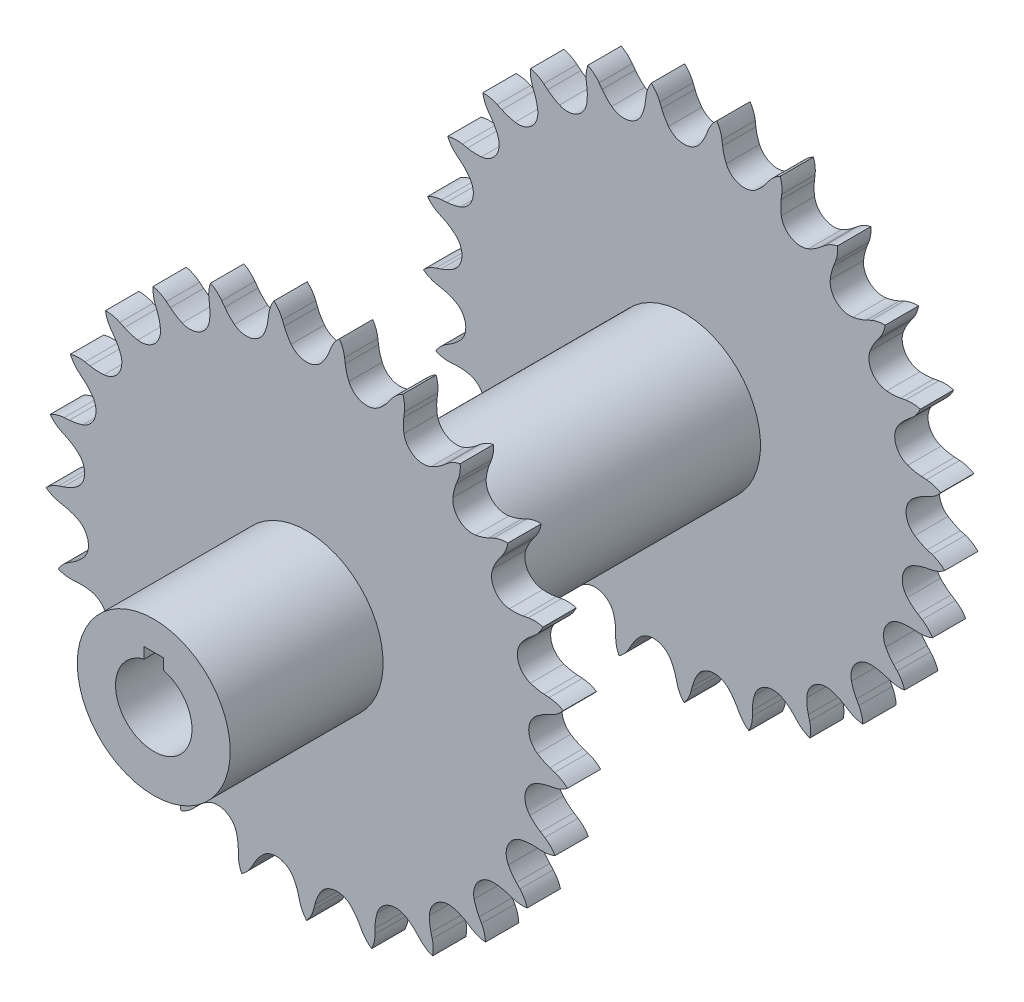
SolidWorks part; units mm, degrees
material "AISI 316 Annealed Stainless Steel Bar (SS)"
ref_plane "Front Plane" through (0, 0, 0) normal (0, 0, 1) x (1, 0, 0)
ref_plane "Top Plane" through (0, 0, 0) normal (0, 1, 0) x (1, 0, 0)
ref_plane "Right Plane" through (0, 0, 0) normal (1, 0, 0) x (0, 0, -1)
sketch "Sketch1" plane through (0, 0, 0) normal (0, 0, 1) x (1, 0, 0)
  line L0 (0, 0) -> (0, 161.8828) construction
  line L1 (6.457, 63.33) -> (6.457, 68.267) construction
  line L2 (89.5524, 63.33) -> (-95.4437, 63.33) construction
  line L3 (6.457, 68.267) -> (0, 68.267)
  line L4 (6.457, 68.267) -> (-4.0675, 60.2204)
  line L5 (6.457, 68.267) -> (-5.8796, 63.3726)
  line L6 (5.8574, 63.3814) -> (6.3512, 64.626)
  line L7 (-5.8574, 63.3814) -> (-6.3512, 64.626)
  line L8 (-14.112, 63.33) -> (-14.112, 61.547) construction
  line L9 (-14.112, 61.547) -> (0, 61.547) construction
  line L10 (0, 0) -> (-19.9508, 157.9268) construction
  line L11 (10.0889, 62.8469) -> (9.9202, 64.1751)
  line L12 (21.4357, 59.9335) -> (22.2235, 61.0162)
  line L13 (25.4014, 58.3634) -> (25.5682, 59.6919)
  line L14 (35.6671, 52.7197) -> (36.6994, 53.5725)
  line L15 (39.1177, 50.2127) -> (39.6097, 51.458)
  line L16 (47.6574, 42.1934) -> (48.8693, 42.7626)
  line L17 (50.3762, 38.907) -> (51.1624, 39.9908)
  line L18 (56.6533, 29.0159) -> (57.9687, 29.2659)
  line L19 (58.4693, 25.1567) -> (59.5004, 26.0109)
  line L20 (62.0894, 14.0152) -> (63.4256, 13.9302)
  line L21 (62.8886, 9.8256) -> (64.0997, 10.3965)
  line L22 (63.6242, -1.8661) -> (64.8973, -2.2807)
  line L23 (63.3563, -6.1228) -> (64.6714, -5.871)
  line L24 (61.1612, -17.6302) -> (62.2912, -18.3484)
  line L25 (59.8432, -21.6866) -> (61.1795, -21.7697)
  line L26 (54.8553, -32.2864) -> (55.7712, -33.2631)
  line L27 (52.5699, -35.8876) -> (53.8436, -36.3005)
  line L28 (45.1026, -44.9141) -> (45.7468, -46.0878)
  line L29 (41.9934, -47.8338) -> (43.1244, -48.5504)
  line L30 (32.5159, -54.7196) -> (32.848, -56.0167)
  line L31 (28.7783, -56.7743) -> (29.6956, -57.7497)
  line L32 (17.8862, -61.0868) -> (17.8852, -62.4258)
  line L33 (13.755, -62.1475) -> (14.4009, -63.3204)
  line L34 (2.1326, -63.6158) -> (1.7987, -64.9124)
  line L35 (-2.1326, -63.6158) -> (-1.7987, -64.9124)
  line L36 (-13.755, -62.1475) -> (-14.4009, -63.3204)
  line L37 (-17.8862, -61.0868) -> (-17.8852, -62.4258)
  line L38 (-28.7783, -56.7743) -> (-29.6956, -57.7497)
  line L39 (-32.5159, -54.7196) -> (-32.848, -56.0167)
  line L40 (-41.9934, -47.8338) -> (-43.1244, -48.5504)
  line L41 (-45.1026, -44.9141) -> (-45.7468, -46.0878)
  line L42 (-52.5699, -35.8876) -> (-53.8436, -36.3005)
  line L43 (-54.8553, -32.2864) -> (-55.7712, -33.2631)
  line L44 (-59.8432, -21.6866) -> (-61.1795, -21.7697)
  line L45 (-61.1612, -17.6302) -> (-62.2912, -18.3484)
  line L46 (-63.3563, -6.1228) -> (-64.6714, -5.871)
  line L47 (-63.6242, -1.8661) -> (-64.8973, -2.2807)
  line L48 (-62.8886, 9.8256) -> (-64.0997, 10.3965)
  line L49 (-62.0894, 14.0152) -> (-63.4256, 13.9302)
  line L50 (-58.4693, 25.1567) -> (-59.5004, 26.0109)
  line L51 (-56.6533, 29.0159) -> (-57.9687, 29.2659)
  line L52 (-50.3762, 38.907) -> (-51.1624, 39.9908)
  line L53 (-47.6574, 42.1934) -> (-48.8693, 42.7626)
  line L54 (-39.1177, 50.2127) -> (-39.6097, 51.458)
  line L55 (-35.6671, 52.7197) -> (-36.6994, 53.5725)
  line L56 (-25.4014, 58.3634) -> (-25.5682, 59.6919)
  line L57 (-21.4357, 59.9335) -> (-22.2235, 61.0162)
  line L58 (-10.0889, 62.8469) -> (-9.9202, 64.1751)
  circle A0 centre (0, 0) radius 63.33 construction
  arc A1 (-5.1081, 63.6787) -> (-5.1158, 63.123) centre (0, 63.33) ccw
  arc A3 (-4.0675, 60.2204) -> (-5.8574, 63.3814) centre (6.457, 68.267) cw
  arc A5 (-4.0675, 60.2204) -> (4.0675, 60.2204) centre (0, 63.33) ccw
  arc A6 (-6.3512, 64.626) -> (-8.5633, 67.7858) centre (-14.112, 61.547) ccw
  arc A7 (4.0675, 60.2204) -> (5.8574, 63.3814) centre (-6.457, 68.267) ccw
  arc A8 (6.3512, 64.626) -> (8.5633, 67.7858) centre (14.112, 61.547) cw
  arc A9 (18.9159, 57.3169) -> (21.4357, 59.9335) centre (10.7232, 67.7281) ccw
  arc A10 (11.0365, 59.34) -> (18.9159, 57.3169) centre (15.7495, 61.3404) ccw
  arc A11 (11.0365, 59.34) -> (10.0889, 62.8469) centre (23.2315, 64.5165) cw
  arc A12 (22.2235, 61.0162) -> (25.152, 63.5266) centre (28.9748, 56.1039) cw
  arc A13 (9.9202, 64.1751) -> (8.5633, 67.7858) centre (1.6375, 63.1229) ccw
  arc A14 (32.5758, 50.812) -> (35.6671, 52.7197) centre (27.2296, 62.9335) ccw
  arc A15 (25.447, 54.7311) -> (32.5758, 50.812) centre (30.5095, 55.4965) ccw
  arc A16 (25.447, 54.7311) -> (25.4014, 58.3634) centre (38.5462, 56.7121) cw
  arc A17 (36.6994, 53.5725) -> (40.1602, 55.2758) centre (42.0169, 47.1355) cw
  arc A18 (25.5682, 59.6919) -> (25.152, 63.5266) centre (17.2841, 60.7326) ccw
  arc A19 (44.1888, 41.1144) -> (47.6574, 42.1934) centre (42.025, 54.1846) ccw
  arc A20 (38.2586, 46.6832) -> (44.1888, 41.1144) centre (43.3524, 46.1656) ccw
  arc A21 (38.2586, 46.6832) -> (39.1177, 50.2127) centre (51.4389, 45.3444) cw
  arc A22 (48.8693, 42.7626) -> (52.645, 43.5517) centre (52.419, 35.2055) cw
  arc A23 (39.6097, 51.458) -> (40.1602, 55.2758) centre (31.8446, 54.5262) ccw
  arc A24 (53.0252, 28.8334) -> (56.6533, 29.0159) centre (54.1799, 42.0311) ccw
  arc A25 (48.6663, 35.702) -> (53.0252, 28.8334) centre (53.4713, 33.9339) ccw
  arc A26 (48.6663, 35.702) -> (50.3762, 38.907) centre (61.0996, 31.1275) cw
  arc A27 (57.9687, 29.2659) -> (61.8219, 29.0912) centre (59.5274, 21.0634) cw
  arc A28 (51.1624, 39.9908) -> (52.645, 43.5517) centre (44.4043, 44.8937) ccw
  arc A29 (58.5299, 14.7407) -> (62.0894, 14.0152) centre (62.9305, 27.2366) ccw
  arc A30 (56.0161, 22.4776) -> (58.5299, 14.7407) centre (60.2304, 19.57) ccw
  arc A31 (56.0161, 22.4776) -> (58.4693, 25.1567) centre (66.9211, 14.9547) cw
  arc A32 (63.4256, 13.9302) -> (67.1144, 12.8028) centre (62.8955, 5.5978) cw
  arc A33 (59.5004, 26.0109) -> (61.8219, 29.0912) centre (54.1738, 32.4404) ccw
  arc A34 (60.357, -0.2782) -> (63.6242, -1.8661) centre (67.7269, 10.7308) ccw
  arc A35 (59.8462, 7.8408) -> (60.357, -0.2782) centre (63.205, 3.9765) ccw
  arc A36 (59.8462, 7.8408) -> (62.8886, 9.8256) centre (68.5377, -2.1577) cw
  arc A37 (64.8973, -2.2807) -> (68.1898, -4.2901) centre (62.3117, -10.2196) cw
  arc A38 (64.0997, 10.3965) -> (67.1144, 12.8028) centre (60.5395, 17.9487) ccw
  arc A39 (58.3915, -15.2797) -> (61.1612, -17.6302) centre (68.2677, -6.4493) ccw
  arc A40 (59.9159, -7.2887) -> (58.3915, -15.2797) centre (62.2083, -11.8669) ccw
  arc A41 (59.9159, -7.2887) -> (63.3563, -6.1228) centre (65.8479, -19.1346) cw
  arc A42 (62.2912, -18.3484) -> (64.9805, -21.1135) centre (57.8125, -25.3948) cw
  arc A43 (64.6714, -5.871) -> (68.1898, -4.2901) centre (63.1012, 2.3293) ccw
  arc A44 (52.7572, -29.321) -> (54.8553, -32.2864) centre (64.5191, -23.2242) ccw
  arc A45 (56.2209, -21.9602) -> (52.7572, -29.321) centre (57.3027, -26.9646) ccw
  arc A46 (56.2209, -21.9602) -> (59.8432, -21.6866) centre (59.0206, -34.9091) cw
  arc A47 (55.7712, -33.2631) -> (57.6884, -36.6101) centre (49.6808, -38.9744) cw
  arc A48 (61.1795, -21.7697) -> (64.9805, -21.1135) centre (61.698, -13.4365) ccw
  arc A49 (43.8079, -41.52) -> (45.1026, -44.9141) centre (56.7165, -38.5398) ccw
  arc A50 (48.9933, -35.2518) -> (43.8079, -41.52) centre (48.7966, -40.3681) ccw
  arc A51 (48.9933, -35.2518) -> (52.5699, -35.8876) centre (48.4848, -48.4902) cw
  arc A52 (45.7468, -46.0878) -> (46.7714, -49.8065) centre (38.4275, -50.105) cw
  arc A53 (53.8436, -36.3005) -> (57.6884, -36.6101) centre (56.4181, -28.3581) ccw
  arc A54 (32.106, -51.1102) -> (32.5159, -54.7196) centre (45.3502, -51.4338) ccw
  arc A55 (38.6874, -46.3285) -> (32.106, -51.1102) centre (37.2244, -51.235) ccw
  arc A56 (38.6874, -46.3285) -> (41.9934, -47.8338) centre (34.9025, -59.0245) cw
  arc A57 (32.848, -56.0167) -> (32.9156, -59.8733) centre (24.7596, -58.0874) cw
  arc A58 (43.1244, -48.5504) -> (46.7714, -49.8065) centre (47.5933, -41.4977) ccw
  arc A59 (18.3867, -57.4889) -> (17.8862, -61.0868) centre (31.1343, -61.0961) ccw
  arc A60 (25.9505, -54.4942) -> (18.3867, -57.4889) centre (23.3133, -58.8827) ccw
  arc A61 (25.9505, -54.4942) -> (28.7783, -56.7743) centre (19.1272, -65.85) cw
  arc A62 (17.8852, -62.4258) -> (16.9916, -66.1781) centre (9.536, -62.4199) cw
  arc A63 (29.6956, -57.7497) -> (32.9156, -59.8733) centre (35.778, -52.03) ccw
  arc A64 (3.5122, -60.2553) -> (2.1326, -63.6158) centre (14.9622, -66.9194) ccw
  arc A65 (11.5831, -59.2357) -> (3.5122, -60.2553) centre (7.9374, -62.8306) ccw
  arc A66 (11.5831, -59.2357) -> (13.755, -62.1475) centre (2.15, -68.538) cw
  arc A67 (1.7987, -64.9124) -> (0, -68.3246) centre (-6.2868, -62.8304) cw
  arc A68 (14.4009, -63.3204) -> (16.9916, -66.1781) centre (21.7146, -59.293) ccw
  arc A69 (-11.5831, -59.2357) -> (-13.755, -62.1475) centre (-2.15, -68.538) ccw
  arc A70 (-3.5122, -60.2553) -> (-11.5831, -59.2357) centre (-7.9374, -62.8306) ccw
  arc A71 (-3.5122, -60.2553) -> (-2.1326, -63.6158) centre (-14.9622, -66.9194) cw
  arc A72 (-14.4009, -63.3204) -> (-16.9916, -66.1781) centre (-21.7146, -59.293) cw
  arc A73 (-1.7987, -64.9124) -> (0, -68.3246) centre (6.2868, -62.8304) ccw
  arc A74 (-25.9505, -54.4942) -> (-28.7783, -56.7743) centre (-19.1272, -65.85) ccw
  arc A75 (-18.3867, -57.4889) -> (-25.9505, -54.4942) centre (-23.3133, -58.8827) ccw
  arc A76 (-18.3867, -57.4889) -> (-17.8862, -61.0868) centre (-31.1343, -61.0961) cw
  arc A77 (-29.6956, -57.7497) -> (-32.9156, -59.8733) centre (-35.778, -52.03) cw
  arc A78 (-17.8852, -62.4258) -> (-16.9916, -66.1781) centre (-9.536, -62.4199) ccw
  arc A79 (-38.6874, -46.3285) -> (-41.9934, -47.8338) centre (-34.9025, -59.0245) ccw
  arc A80 (-32.106, -51.1102) -> (-38.6874, -46.3285) centre (-37.2244, -51.235) ccw
  arc A81 (-32.106, -51.1102) -> (-32.5159, -54.7196) centre (-45.3502, -51.4338) cw
  arc A82 (-43.1244, -48.5504) -> (-46.7714, -49.8065) centre (-47.5933, -41.4977) cw
  arc A83 (-32.848, -56.0167) -> (-32.9156, -59.8733) centre (-24.7596, -58.0874) ccw
  arc A84 (-48.9933, -35.2518) -> (-52.5699, -35.8876) centre (-48.4848, -48.4902) ccw
  arc A85 (-43.8079, -41.52) -> (-48.9933, -35.2518) centre (-48.7966, -40.3681) ccw
  arc A86 (-43.8079, -41.52) -> (-45.1026, -44.9141) centre (-56.7165, -38.5398) cw
  arc A87 (-53.8436, -36.3005) -> (-57.6884, -36.6101) centre (-56.4181, -28.3581) cw
  arc A88 (-45.7468, -46.0878) -> (-46.7714, -49.8065) centre (-38.4275, -50.105) ccw
  arc A89 (-56.2209, -21.9602) -> (-59.8432, -21.6866) centre (-59.0206, -34.9091) ccw
  arc A90 (-52.7572, -29.321) -> (-56.2209, -21.9602) centre (-57.3027, -26.9646) ccw
  arc A91 (-52.7572, -29.321) -> (-54.8553, -32.2864) centre (-64.5191, -23.2242) cw
  arc A92 (-61.1795, -21.7697) -> (-64.9805, -21.1135) centre (-61.698, -13.4365) cw
  arc A93 (-55.7712, -33.2631) -> (-57.6884, -36.6101) centre (-49.6808, -38.9744) ccw
  arc A94 (-59.9159, -7.2887) -> (-63.3563, -6.1228) centre (-65.8479, -19.1346) ccw
  arc A95 (-58.3915, -15.2797) -> (-59.9159, -7.2887) centre (-62.2083, -11.8669) ccw
  arc A96 (-58.3915, -15.2797) -> (-61.1612, -17.6302) centre (-68.2677, -6.4493) cw
  arc A97 (-64.6714, -5.871) -> (-68.1898, -4.2901) centre (-63.1012, 2.3293) cw
  arc A98 (-62.2912, -18.3484) -> (-64.9805, -21.1135) centre (-57.8125, -25.3948) ccw
  arc A99 (-59.8462, 7.8408) -> (-62.8886, 9.8256) centre (-68.5377, -2.1577) ccw
  arc A100 (-60.357, -0.2782) -> (-59.8462, 7.8408) centre (-63.205, 3.9765) ccw
  arc A101 (-60.357, -0.2782) -> (-63.6242, -1.8661) centre (-67.7269, 10.7308) cw
  arc A102 (-64.0997, 10.3965) -> (-67.1144, 12.8028) centre (-60.5395, 17.9487) cw
  arc A103 (-64.8973, -2.2807) -> (-68.1898, -4.2901) centre (-62.3117, -10.2196) ccw
  arc A104 (-56.0161, 22.4776) -> (-58.4693, 25.1567) centre (-66.9211, 14.9547) ccw
  arc A105 (-58.5299, 14.7407) -> (-56.0161, 22.4776) centre (-60.2304, 19.57) ccw
  arc A106 (-58.5299, 14.7407) -> (-62.0894, 14.0152) centre (-62.9305, 27.2366) cw
  arc A107 (-59.5004, 26.0109) -> (-61.8219, 29.0912) centre (-54.1738, 32.4404) cw
  arc A108 (-63.4256, 13.9302) -> (-67.1144, 12.8028) centre (-62.8955, 5.5978) ccw
  arc A109 (-48.6663, 35.702) -> (-50.3762, 38.907) centre (-61.0996, 31.1275) ccw
  arc A110 (-53.0252, 28.8334) -> (-48.6663, 35.702) centre (-53.4713, 33.9339) ccw
  arc A111 (-53.0252, 28.8334) -> (-56.6533, 29.0159) centre (-54.1799, 42.0311) cw
  arc A112 (-51.1624, 39.9908) -> (-52.645, 43.5517) centre (-44.4043, 44.8937) cw
  arc A113 (-57.9687, 29.2659) -> (-61.8219, 29.0912) centre (-59.5274, 21.0634) ccw
  arc A114 (-38.2586, 46.6832) -> (-39.1177, 50.2127) centre (-51.4389, 45.3444) ccw
  arc A115 (-44.1888, 41.1144) -> (-38.2586, 46.6832) centre (-43.3524, 46.1656) ccw
  arc A116 (-44.1888, 41.1144) -> (-47.6574, 42.1934) centre (-42.025, 54.1846) cw
  arc A117 (-39.6097, 51.458) -> (-40.1602, 55.2758) centre (-31.8446, 54.5262) cw
  arc A118 (-48.8693, 42.7626) -> (-52.645, 43.5517) centre (-52.419, 35.2055) ccw
  arc A119 (-25.447, 54.7311) -> (-25.4014, 58.3634) centre (-38.5462, 56.7121) ccw
  arc A120 (-32.5758, 50.812) -> (-25.447, 54.7311) centre (-30.5095, 55.4965) ccw
  arc A121 (-32.5758, 50.812) -> (-35.6671, 52.7197) centre (-27.2296, 62.9335) cw
  arc A122 (-25.5682, 59.6919) -> (-25.152, 63.5266) centre (-17.2841, 60.7326) cw
  arc A123 (-36.6994, 53.5725) -> (-40.1602, 55.2758) centre (-42.0169, 47.1355) ccw
  arc A124 (-11.0365, 59.34) -> (-10.0889, 62.8469) centre (-23.2315, 64.5165) ccw
  arc A125 (-18.9159, 57.3169) -> (-11.0365, 59.34) centre (-15.7495, 61.3404) ccw
  arc A126 (-18.9159, 57.3169) -> (-21.4357, 59.9335) centre (-10.7232, 67.7281) cw
  arc A127 (-9.9202, 64.1751) -> (-8.5633, 67.7858) centre (-1.6375, 63.1229) cw
  arc A128 (-22.2235, 61.0162) -> (-25.152, 63.5266) centre (-28.9748, 56.1039) ccw
  circle A129 centre (0, 0) radius 68.3246 construction
  point P342 (0, 0)
  dimension "D1" = 126.66
  dimension "D2" = 10.24
  dimension "D8" = 1.783
  dimension "D9" = 14.112
  dimension "D10" = 7.2
  dimension "D12" = 136.6492
  dimension "D3" = 6.457
  dimension "D4" = 4.937
  dimension "D5" = 37.4
  dimension "D6" = 15.76
  dimension "D7" = 13.272
  dimension "D11" = 25
extrude "Boss-Extrude1" add sketch "Sketch1" along normal blind 8.712 contours L57 A128 L2 A122 L56 A119 A120 A121 L55 A123 A117 L54 A114 A115 A116 L53 A118 A112 L52 A109 A110 A111 L51 A113 A107 L50 A104 A105 A106 L49 A108 A102 L48 A99 A100 A101 L47 A103 A97 L46 A94 A95 A96 L45 A98 A92 L44 A89 A90 A91 L43
sketch "Sketch2" plane through (0, 0, 8.712) normal (0, 0, 1) x (1, 0, 0)
  circle A0 centre (0, 0) radius 20
  dimension "D1" = 40
extrude "Boss-Extrude2" add sketch "Sketch2" along normal blind 90
ref_plane "Plane1" through (0, 0, 53.712) normal (0, 0, 1) x (1, 0, 0)
mirror "Mirror1" about plane through (0, 0, 53.712) normal (0, 0, 1) of "Boss-Extrude1"
sketch "Sketch4" plane through (0, 0, 107.424) normal (0, 0, 1) x (1, 0, 0)
  circle A0 centre (0, 0) radius 20
  dimension "D1" = 40
extrude "Boss-Extrude3" add sketch "Sketch4" along normal blind 40
sketch "Sketch5" plane through (0, 0, 147.424) normal (0, 0, 1) x (1, 0, 0)
  line L1 (-2.5, 12.5) -> (2.5, 12.5)
  line L2 (-2.5, 12.5) -> (-2.5, 9.6825)
  line L4 (2.5, 12.5) -> (2.5, 9.6825)
  line L5 (-2.5, 12.5) -> (2.5, 7.5) construction
  line L6 (-2.5, 7.5) -> (2.5, 12.5) construction
  arc A0 (-2.5, 9.6825) -> (2.5, 9.6825) centre (0, 0) ccw
  point P3 (0, 10)
  dimension "D1" = 20
  dimension "D2" = 5
  dimension "D3" = 5
extrude "Cut-Extrude1" cut sketch "Sketch5" against normal blind 138.712 and the other way through all
ref_plane "Plane2" through (0, 0, 4.356) normal (0, 0, 1) x (1, 0, 0)
ref_plane "Plane3" through (0, 0, 103.068) normal (0, 0, -1) x (-1, 0, 0)
